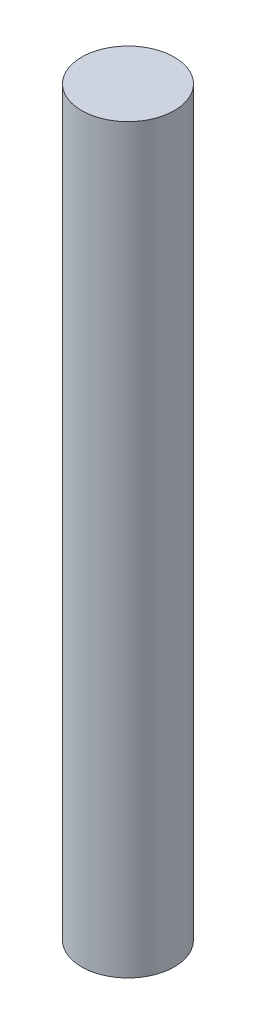
SolidWorks part; units mm, degrees
ref_plane "Front Plane" through (0, 0, 0) normal (0, 0, 1) x (1, 0, 0)
ref_plane "Top Plane" through (0, 0, 0) normal (0, 1, 0) x (1, 0, 0)
ref_plane "Right Plane" through (0, 0, 0) normal (1, 0, 0) x (0, 0, -1)
sketch "Sketch1" plane through (0, 0, 0) normal (0, 1, 0) x (1, 0, 0)
  circle A0 centre (0, 0) radius 1
  dimension "D1" = 2
extrude "Boss-Extrude1" add sketch "Sketch1" along normal blind 16
